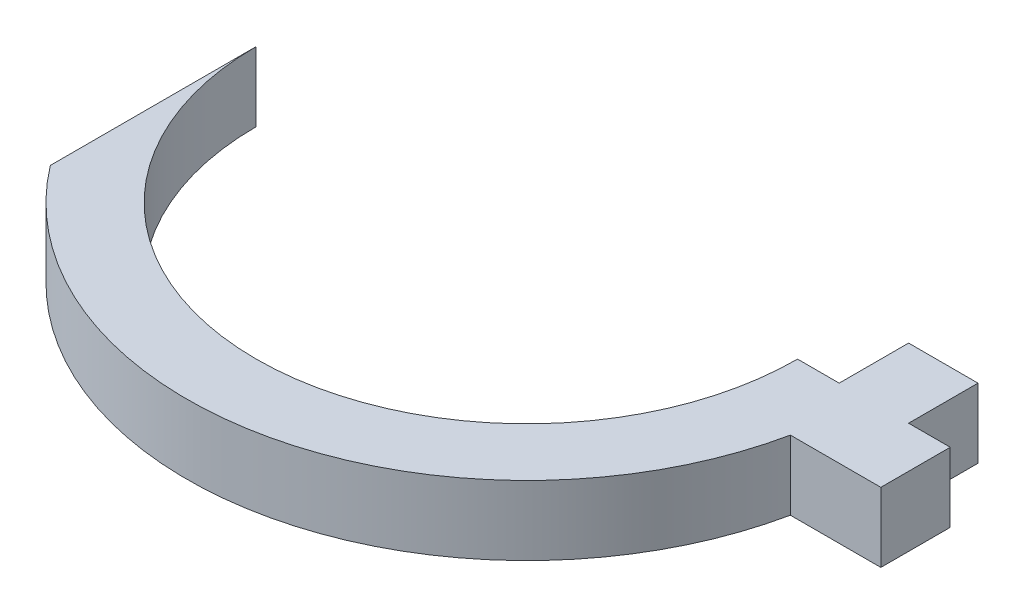
SolidWorks part; units mm, degrees
ref_plane "Front Plane" through (0, 0, 0) normal (0, 0, 1) x (1, 0, 0)
ref_plane "Top Plane" through (0, 0, 0) normal (0, 1, 0) x (1, 0, 0)
ref_plane "Right Plane" through (0, 0, 0) normal (1, 0, 0) x (0, 0, -1)
sketch "Sketch1" plane through (0, 0, 0) normal (0, 1, 0) x (1, 0, 0)
  line L0 (-6.35, -6.35) -> (-6.35, 0)
  line L1 (-6.35, 0) -> (0, 0)
  line L2 (0, 0) -> (0, -6.35)
  line L3 (-6.35, -6.35) -> (-10.16, -6.35)
  line L4 (-59.69, -6.35) -> (-59.69, -25.1871)
  line L5 (0, -6.35) -> (3.81, -6.35)
  line L6 (3.81, -6.35) -> (3.81, -12.7)
  line L7 (3.81, -12.7) -> (-4.4649, -12.7)
  arc A0 (-10.16, -6.35) -> (-59.69, -6.35) centre (-34.925, -6.35) cw
  arc A1 (-59.69, -25.1871) -> (-4.4649, -12.7) centre (-34.925, -6.35) ccw
  dimension "D1" = 24.765
  dimension "D5" = 6.35
  dimension "D4" = 6.35
  dimension "D2" = 3.81
  dimension "D3" = 6.35
  dimension "D6" = 3.81
extrude "Boss-Extrude1" add sketch "Sketch1" along normal blind 6.35
equation "\"Ball Diameter\"= 1.75in"
equation "\"Sheet Thickness\"= 0.25in"
equation "\"Screw Diameter\"= .17in"
equation "\"Robot Diameter\"= 14in"
equation "\"Castor Screw Diameter\"= 0.22in"
equation "\"Wheel Diameter\" = 4in"
equation "\"Nut Diameter\" = 8.4mm"
equation "\"Nut Height\" = 2.9mm"
equation "\"Screw Height\" = 0.55in"
equation "\"Pulley Diameter\" = 1in"
equation "\"Reactor Height\" = 14in"
equation "\"Elevator Height\" = 11.5in"
equation "\"Elevator Width\" = \"Ball Diameter\" + 0.25in"
equation "\"Elevator Bearing Diameter\" = sqr(2*(\"Sheet Thickness\"^2)) + 0.2in"
equation "\"Elevator Axle Endcap Diameter\" = \"Pulley Diameter\" + 0.25in"
equation "\"Elevator Axle Length\" = \"Elevator Width\" + 8*\"Sheet Thickness\""
equation "\"Elevator Clearance from Axis\" = (\"Pulley Diameter\"/2) + \"Ball Diameter\" + 0.5in"
equation "\"D1@Sketch1\"=\"Ball Radius\" + 0.1in"
equation "\"D3@Sketch1\"=\"Sheet Thickness\""
equation "\"D4@Sketch1\"=\"Sheet Thickness\""
equation "\"D5@Sketch1\"=\"Sheet Thickness\""
equation "\"D1@Boss-Extrude1\"=\"Sheet Thickness\""
equation "\"Ball Radius\" = \"Ball Diameter\"/2"
equation "\"Claw Horizontal Seperation\" = (\"Elevator Width\"/2) - (1.5 * \"Sheet Thickness\") - 0.15in"
